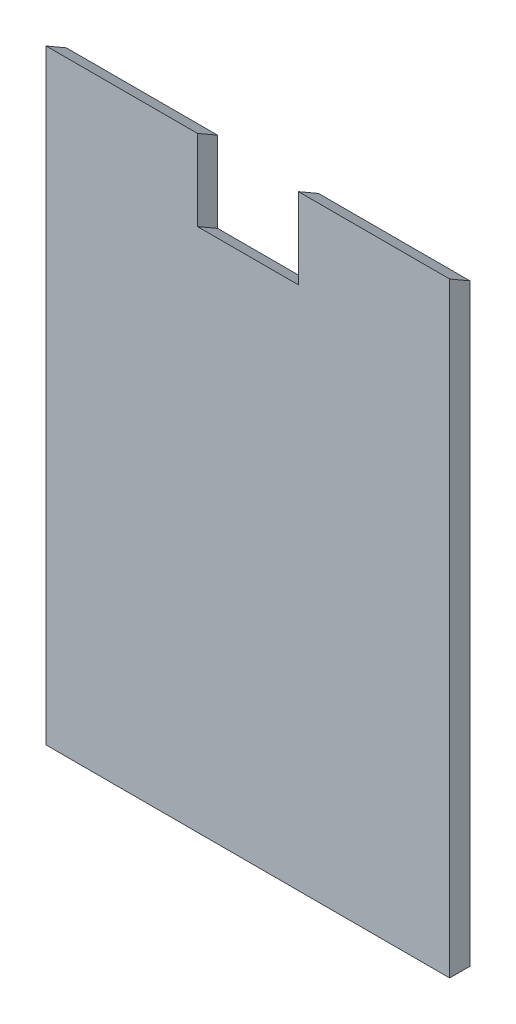
SolidWorks part; units mm, degrees
ref_plane "Front Plane" through (0, 0, 0) normal (0, 0, 1) x (1, 0, 0)
ref_plane "Top Plane" through (0, 0, 0) normal (0, 1, 0) x (1, 0, 0)
ref_plane "Right Plane" through (0, 0, 0) normal (1, 0, 0) x (0, 0, -1)
sketch "Sketch1" plane through (0, 0, 0) normal (0, 0, 1) x (1, 0, 0)
  line L0 (0, -234.1574) -> (0, 234.1574) construction
  line L1 (127, -190.5) -> (-127, -190.5)
  line L2 (127, -190.5) -> (127, 190.5)
  line L3 (127, 190.5) -> (31.75, 190.5)
  line L4 (-127, -190.5) -> (-127, 190.5)
  line L5 (127, -190.5) -> (-127, 190.5) construction
  line L6 (127, 190.5) -> (-127, -190.5) construction
  line L7 (-31.75, 139.7) -> (31.75, 139.7)
  line L8 (31.75, 139.7) -> (31.75, 190.5)
  line L9 (-31.75, 139.7) -> (-31.75, 190.5)
  line L10 (-31.75, 190.5) -> (-127, 190.5)
  point P0 (0, 0)
  point P9 (0, 0)
  point P12 (0, 139.7)
  dimension "D1" = 381
  dimension "D2" = 254
  dimension "D3" = 63.5
  dimension "D4" = 50.8
extrude "Boss-Extrude1" add sketch "Sketch1" along normal mid plane 12.7
sketch "Sketch4" plane through (0, 0, 0) normal (1, 0, 0) x (0, 0, -1)
  line L0 (0, -262.6115) -> (0, 262.6115) construction
  line L1 (-169.2802, 0) -> (169.2802, 0) construction
  line L2 (-88.5479, 139.7) -> (88.5479, 139.7) construction
  line L3 (-6.35, 190.5) -> (6.35, 190.5) construction
  line L8 (-6.35, 139.7) -> (6.35, 139.7)
  line L9 (6.35, 139.7) -> (6.35, 132.3677)
  line L12 (-6.35, 139.7) -> (6.35, 132.3677)
  line L13 (6.35, -190.5) -> (6.35, 190.5) construction
  line L14 (-6.35, 190.5) -> (6.35, 190.5)
  line L15 (6.35, 190.5) -> (6.35, 183.1677)
  line L16 (-6.35, 190.5) -> (6.35, 183.1677)
  point P4 (0, 0)
  point P8 (0, 0)
  point P11 (0, 139.7)
  dimension "D1" = 50.8
  dimension "D2" = 30
  dimension "D3" = 30
extrude "Cut-Extrude1" cut sketch "Sketch4" against normal mid plane 63.5
sketch "Sketch5" plane through (0, 0, 0) normal (1, 0, 0) x (0, 0, -1)
  line L0 (-6.35, 190.5) -> (6.35, 190.5)
  line L1 (6.35, 190.5) -> (6.35, 183.1677)
  line L3 (-6.35, 190.5) -> (6.35, 183.1677)
  dimension "D1" = 30
extrude "Cut-Extrude2" cut sketch "Sketch5" against normal mid plane 254
